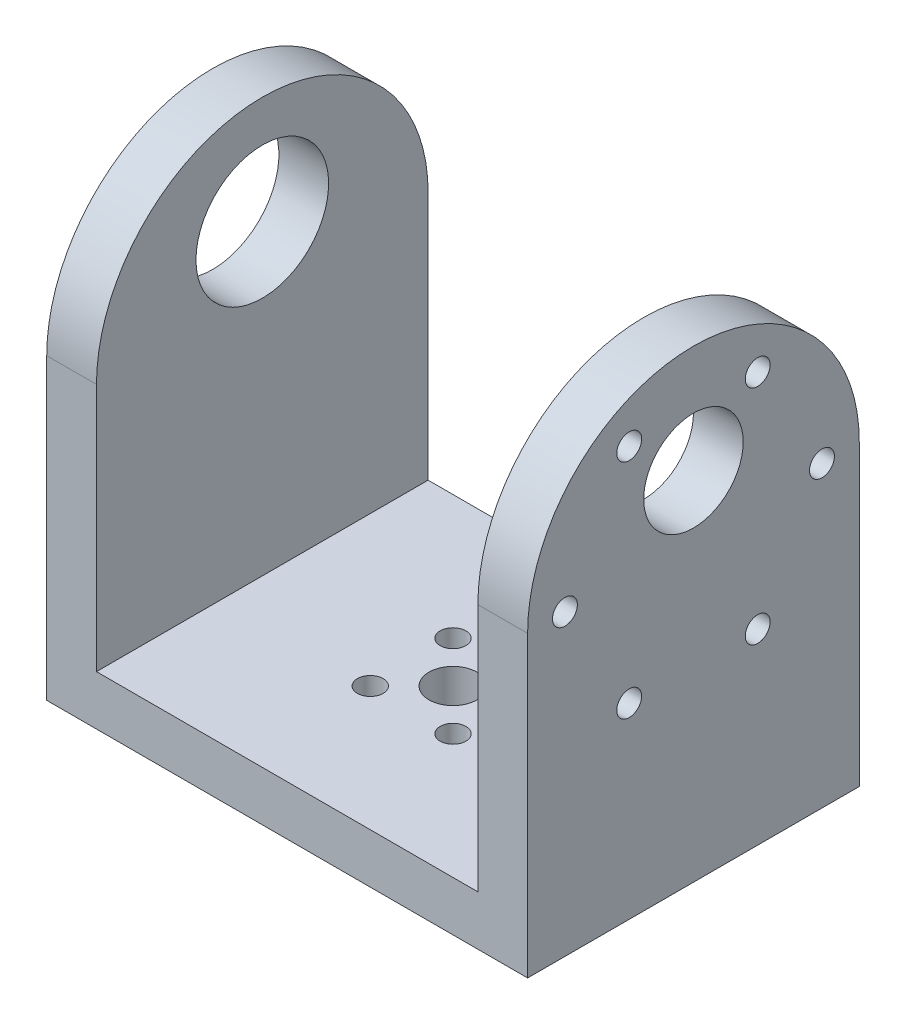
SolidWorks part; units mm, degrees
ref_plane "Front Plane" through (0, 0, 0) normal (0, 0, 1) x (1, 0, 0)
ref_plane "Top Plane" through (0, 0, 0) normal (0, 1, 0) x (1, 0, 0)
ref_plane "Right Plane" through (0, 0, 0) normal (1, 0, 0) x (0, 0, -1)
sketch "Sketch2" plane through (0, 0, 0) normal (0, 1, 0) x (1, 0, 0)
  line L1 (-21.5, 61.5708) -> (28.5, 61.5708)
  line L2 (-21.5, 61.5708) -> (-21.5, 21.5708)
  line L3 (-21.5, 21.5708) -> (28.5, 21.5708)
  line L4 (28.5, 61.5708) -> (28.5, 21.5708)
  point P0 (0, 0)
  dimension "D1" = 50
  dimension "D2" = 40
extrude "Boss-Extrude2" add sketch "Sketch2" along normal blind 2 and the other way blind 4
sketch "Sketch4" plane through (-21.5, 0, 0) normal (-1, 0, 0) x (0, 0, 1)
  line L1 (-21.5708, 2) -> (-61.5708, 2)
  line L2 (-21.5708, 2) -> (-21.5708, 32)
  line L4 (-61.5708, 2) -> (-61.5708, 32)
  arc A0 (-21.5708, 32) -> (-61.5708, 32) centre (-41.5708, 32) ccw
  point P5 (-41.5708, 52)
  dimension "D1" = 20
  dimension "D2" = 50
extrude "Boss-Extrude3" add sketch "Sketch4" against normal blind 2 and the other way blind 4
sketch "Sketch5" plane through (28.5, 0, 0) normal (1, 0, 0) x (0, 0, -1)
  line L1 (21.5708, -4) -> (61.5708, -4)
  line L2 (21.5708, -4) -> (21.5708, 32)
  line L4 (61.5708, -4) -> (61.5708, 32)
  arc A0 (61.5708, 32) -> (21.5708, 32) centre (41.5708, 32) ccw
extrude "Boss-Extrude4" add sketch "Sketch5" against normal blind 2 and the other way blind 4
sketch "Sketch7" plane through (-21.5, 0, 0) normal (-1, 0, 0) x (0, 0, 1)
  line L0 (19.236, 32) -> (-43.1388, 32) construction
  circle A0 centre (-41.5708, 32) radius 15.5 construction
  circle A1 centre (-26.0708, 32) radius 1.5
  circle A2 centre (-33.8208, 18.5766) radius 1.5
  circle A3 centre (-49.3208, 18.5766) radius 1.5
  circle A4 centre (-57.0708, 32) radius 1.5
  circle A5 centre (-49.3208, 45.4234) radius 1.5
  circle A6 centre (-33.8208, 45.4234) radius 1.5
  circle A7 centre (-41.5708, 39) radius 6
  point P18 (-41.5708, 32)
  dimension "D1" = 31
  dimension "D2" = 3
  dimension "D7" = 12
  dimension "D4" = 13.4234
  dimension "D5" = 7.75
  dimension "D6" = 7
  dimension "D3" = 6
extrude "Cut-Extrude1" cut sketch "Sketch7" against normal blind 92 and the other way blind 10
sketch "Sketch8" plane through (0, 2, 0) normal (0, 1, 0) x (1, 0, 0)
  line L1 (26.5, 21.5708) -> (26.5, 61.5708) construction
  line L2 (-19.5, 21.5708) -> (26.5, 21.5708) construction
  circle A0 centre (3.5, 41.5708) radius 2.9
  circle A2 centre (-1.49, 46.5608) radius 1.55
  circle A3 centre (8.49, 46.5608) radius 1.55
  circle A6 centre (-1.49, 36.5808) radius 1.55
  circle A7 centre (8.49, 36.5808) radius 1.55
  point P14 (26.5, 41.5708)
  point P15 (3.5, 21.5708)
  dimension "D2" = 4.99
  dimension "D6" = 5.8
  dimension "D1" = 3.1
  dimension "D4" = 4.99
  dimension "D5" = 4.99
  dimension "D3" = 4.99
extrude "Cut-Extrude2" cut sketch "Sketch8" against normal blind 92
sketch "Sketch9" plane through (0, 0, -21.5708) normal (0, 0, 1) x (1, 0, 0)
sketch "Sketch10" plane through (0, 0, -21.5708) normal (0, 0, 1) x (1, 0, 0)
  line L1 (-25.5, 2) -> (-21.5, 2)
  line L2 (-25.5, 2) -> (-25.5, -4)
  line L3 (-25.5, -4) -> (-21.5, -4)
  line L4 (-21.5, 2) -> (-21.5, -4)
extrude "Boss-Extrude5" add sketch "Sketch10" against normal up to vertex (40 mm away)
sketch "Sketch11" plane through (0, -4, 0) normal (0, -1, 0) x (-1, 0, 0)
  line L0 (-32.5, 61.5708) -> (25.5, 61.5708) construction
  line L1 (-23.3799, 21.5708) -> (-23.3799, 61.5708) construction
  point P0 (-23.3799, 61.5708)
sketch "Çizim1" plane through (-19.5, 0, 0) normal (1, 0, 0) x (0, 0, -1)
  circle A0 centre (26.0708, 32) radius 2.3132
  circle A1 centre (33.8208, 45.4234) radius 2.3132
  circle A2 centre (49.3208, 45.4234) radius 2.3132
  circle A3 centre (57.0708, 32) radius 2.3132
  circle A4 centre (49.3208, 18.5766) radius 2.3132
  circle A5 centre (33.8208, 18.5766) radius 2.3132
  point P19 (41.5708, 32)
  dimension "D1" = 6
extrude "Kes-Ekstrüzyon1" cut sketch "Çizim1" along normal blind 48
sketch "Çizim2" plane through (-25.5, 0, 0) normal (-1, 0, 0) x (0, 0, 1)
  line L3 (-21.5708, -4) -> (-21.5708, 32)
  line L4 (-61.5708, 32) -> (-61.5708, -4)
  line L5 (-61.5708, -4) -> (-21.5708, -4)
  line L6 (-21.5708, -4) -> (-21.5708, 32)
  line L7 (-61.5708, 32) -> (-61.5708, -4)
  line L8 (-61.5708, -4) -> (-21.5708, -4)
  arc A1 (-21.5708, 32) -> (-61.5708, 32) centre (-41.5708, 32) ccw
  arc A2 (-21.5708, 32) -> (-61.5708, 32) centre (-41.5708, 32) ccw
  dimension "D1" = 0
extrude "Yükseklik-Ekstrüzyon1" add sketch "Çizim2" against normal blind 6
sketch "Çizim3" plane through (-25.5, 0, 0) normal (-1, 0, 0) x (0, 0, 1)
  circle A1 centre (-41.5708, 39) radius 8
  dimension "D2" = 16
extrude "Kes-Ekstrüzyon2" cut sketch "Çizim3" against normal blind 6
